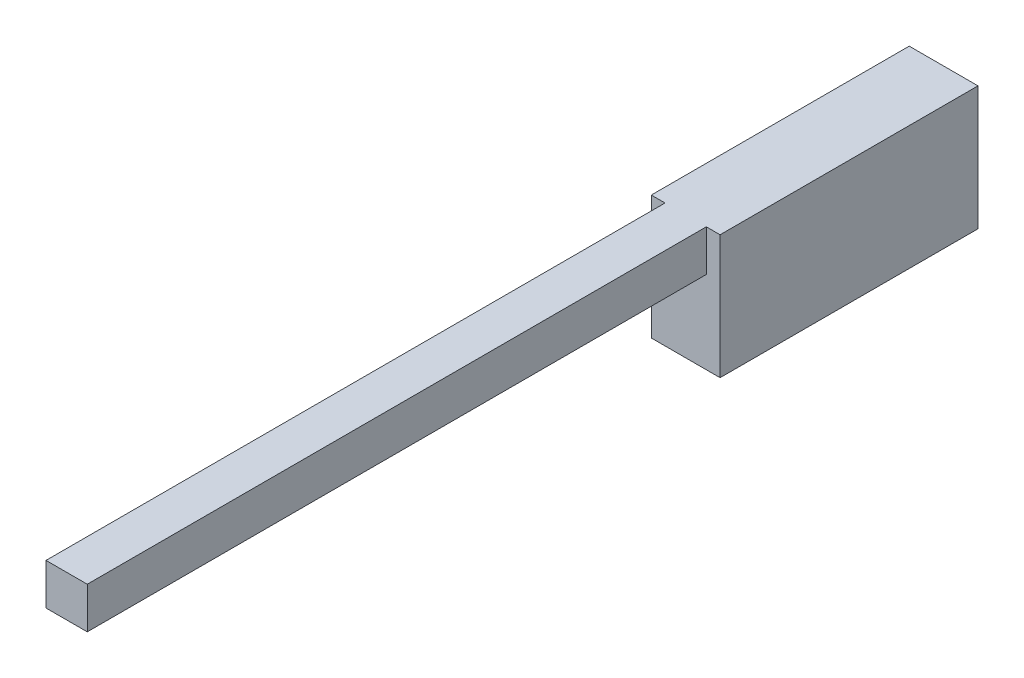
SolidWorks part; units mm, degrees
ref_plane "Front Plane" through (0, 0, 0) normal (0, 0, 1) x (1, 0, 0)
ref_plane "Top Plane" through (0, 0, 0) normal (0, 1, 0) x (1, 0, 0)
ref_plane "Right Plane" through (0, 0, 0) normal (1, 0, 0) x (0, 0, -1)
sketch "Sketch2" plane through (0, 0, 0) normal (0, 0, 1) x (1, 0, 0)
  line L1 (0, 0) -> (20, 0)
  line L2 (0, 0) -> (0, 36)
  line L3 (0, 36) -> (20, 36)
  line L4 (20, 0) -> (20, 36)
  dimension "D1" = 36
  dimension "D2" = 20
extrude "Boss-Extrude1" add sketch "Sketch2" along normal blind 75
sketch "Sketch3" plane through (0, 0, 75) normal (0, 0, 1) x (1, 0, 0)
  line L0 (20, 36) -> (0, 36) construction
  line L1 (4, 36) -> (16, 36)
  line L2 (4, 36) -> (4, 24)
  line L3 (4, 24) -> (16, 24)
  line L4 (16, 36) -> (16, 24)
  line L5 (0, 36) -> (4, 36) construction
  line L6 (16, 36) -> (20, 36) construction
  dimension "D1" = 12
  dimension "D2" = 12
extrude "Boss-Extrude2" add sketch "Sketch3" along normal blind 180
